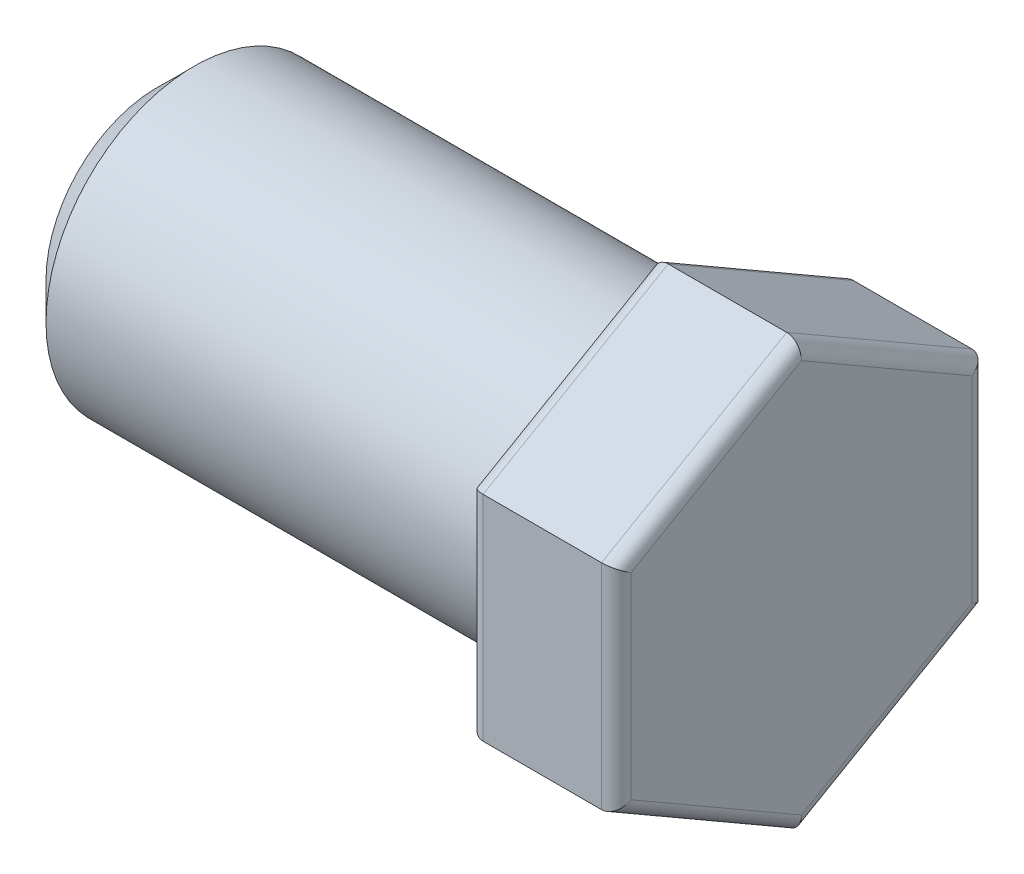
SolidWorks part; units mm, degrees
material "Cast Stainless Steel"
ref_plane "Front Plane" through (0, 0, 0) normal (0, 0, 1) x (1, 0, 0)
ref_plane "Top Plane" through (0, 0, 0) normal (0, 1, 0) x (1, 0, 0)
ref_plane "Right Plane" through (0, 0, 0) normal (1, 0, 0) x (0, 0, -1)
sketch "Sketch1" plane through (0, 0, 0) normal (1, 0, 0) x (0, 0, -1)
  line L0 (2.5, 1.4434) -> (0, 2.8868)
  line L1 (0, 2.8868) -> (-2.5, 1.4434)
  line L2 (-2.5, 1.4434) -> (-2.5, -1.4434)
  line L3 (-2.5, -1.4434) -> (0, -2.8868)
  line L4 (0, -2.8868) -> (2.5, -1.4434)
  line L5 (2.5, -1.4434) -> (2.5, 1.4434)
  circle A0 centre (0, 0) radius 2.5 construction
  dimension "D1" = 5
  dimension "D2" = 2.5
extrude "Boss-Extrude1" add sketch "Sketch1" along normal mid plane 2
fillet "Fillet1" radius 0.2 12 edges at (1, -2.1651, -1.25) (1, -2.1651, 1.25) (1, 0, 2.5) (1, 2.1651, 1.25) (1, 2.1651, -1.25) (1, 0, -2.5) (-1, 2.1651, -1.25) (-1, 2.1651, 1.25) (-1, 0, 2.5) (-1, -2.1651, 1.25) (-1, -2.1651, -1.25) (-1, 0, -2.5)
sketch "Sketch2" plane through (-1, 0, 0) normal (-1, 0, 0) x (0, 0, 1)
  circle A0 centre (0, 0) radius 2
  dimension "D1" = 4
extrude "Boss-Extrude2" add sketch "Sketch2" along normal blind 6.7
chamfer "Chamfer1" distance 0.5 angle 45 1 edges at (-7.7, 0, 2)
fillet "Fillet2" radius 0.2 1 edges at (-1, 0, -2)
